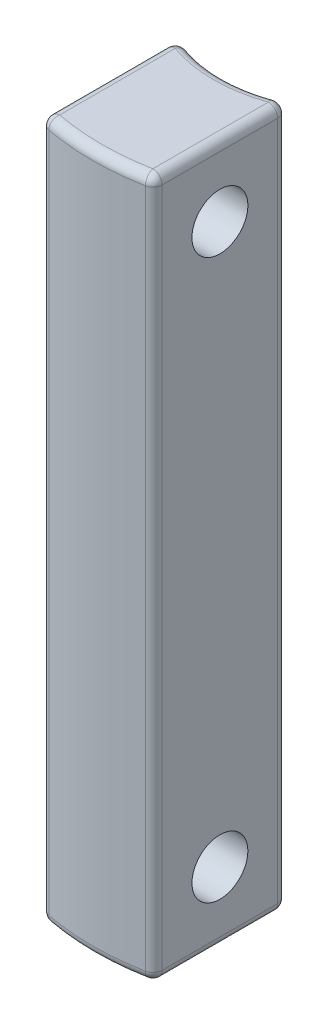
SolidWorks part; units mm, degrees
ref_plane "前视基准面" through (0, 0, 0) normal (0, 0, 1) x (1, 0, 0)
ref_plane "上视基准面" through (0, 0, 0) normal (0, 1, 0) x (1, 0, 0)
ref_plane "右视基准面" through (0, 0, 0) normal (1, 0, 0) x (0, 0, -1)
other "Configuration Table"
sketch "草图1" plane through (0, 0, 0) normal (0, 1, 0) x (1, 0, 0)
  line L0 (0, 14) -> (0, 28) construction
  line L2 (6, -14.1421) -> (6, -26.533)
  line L3 (-6, -14.1421) -> (-6, -26.533)
  arc A0 (-5.1852, -27.5157) -> (5.1852, -27.5157) centre (0, 0) ccw
  arc A1 (-4.6667, -13.1993) -> (4.6667, -13.1993) centre (0, 0) ccw
  arc A2 (-5.1852, -27.5157) -> (-6, -26.533) centre (-5, -26.533) cw
  arc A3 (5.1852, -27.5157) -> (6, -26.533) centre (5, -26.533) ccw
  arc A4 (4.6667, -13.1993) -> (6, -14.1421) centre (5, -14.1421) cw
  arc A5 (-6, -14.1421) -> (-4.6667, -13.1993) centre (-5, -14.1421) cw
  dimension "D1" = 56
  dimension "D2" = 28
  dimension "D3" = 1
extrude "凸台-拉伸1" add sketch "草图1" along normal blind 75
fillet "圆角1" radius 1 16 edges at (0, 0, 28) (5.7698, 0, 27.1713) (6, 0, 20.3376) (5.5774, 0, 13.3256) (0, 0, 14) (-5.5774, 0, 13.3256) (-6, 0, 20.3376) (-5.7698, 0, 27.1713) (-6, 75, 20.3376) (-5.5774, 75, 13.3256) (0, 75, 14) (5.5774, 75, 13.3256) (6, 75, 20.3376) (5.7698, 75, 27.1713) (0, 75, 28) (-5.7698, 75, 27.1713)
sketch "草图2" plane through (6, 0, 0) normal (1, 0, 0) x (0, 0, -1)
  line L0 (-13.1421, 37.5) -> (-28.3511, 37.5) construction
  line L1 (-13.1421, 1) -> (-13.1421, 74) construction
  line L2 (-20.3376, 74) -> (-20.3376, 59.5545) construction
  line L3 (-14.1421, 74) -> (-26.533, 74) construction
  circle A1 centre (-20.3376, 7.5) radius 3
  circle A2 centre (-20.3376, 67.5) radius 3
  dimension "D1" = 6
  dimension "D2" = 60
extrude "切除-拉伸1" cut sketch "草图2" against normal through all
